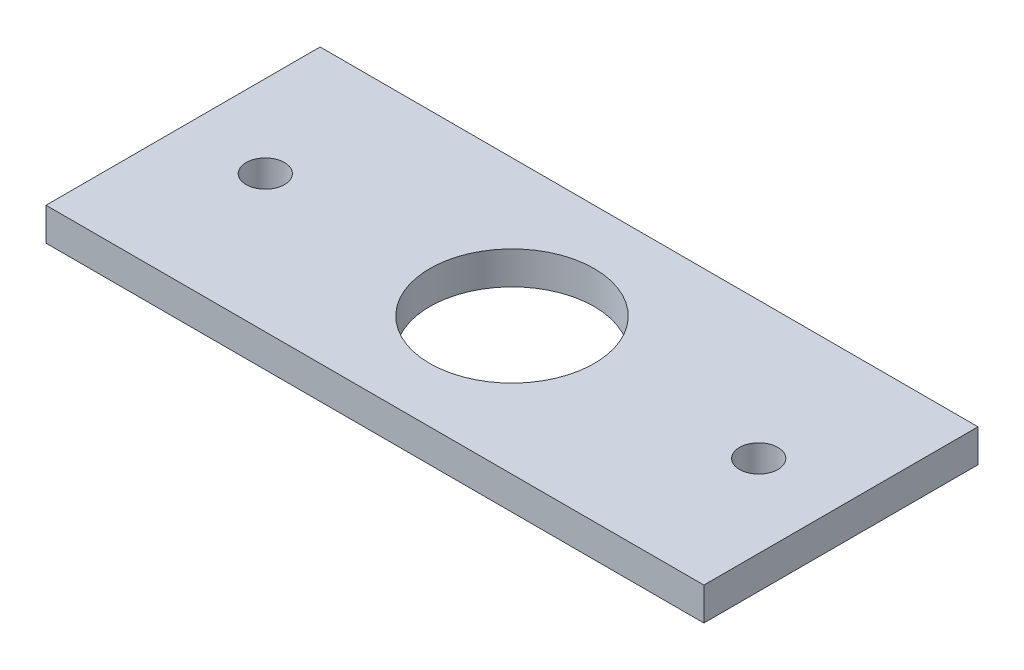
SolidWorks part; units mm, degrees
ref_plane "Front Plane" through (0, 0, 0) normal (0, 0, 1) x (1, 0, 0)
ref_plane "Top Plane" through (0, 0, 0) normal (0, 1, 0) x (1, 0, 0)
ref_plane "Right Plane" through (0, 0, 0) normal (1, 0, 0) x (0, 0, -1)
sketch "Sketch1" plane through (0, 0, 0) normal (0, 1, 0) x (1, 0, 0)
  line L0 (0, -55) -> (0, 55) construction
  line L1 (30, -12.5) -> (-30, -12.5)
  line L2 (30, -12.5) -> (30, 12.5)
  line L3 (30, 12.5) -> (-30, 12.5)
  line L4 (-30, -12.5) -> (-30, 12.5)
  line L5 (30, -12.5) -> (-30, 12.5) construction
  line L6 (30, 12.5) -> (-30, -12.5) construction
  line L7 (-22.5, 0) -> (0, 0) construction
  circle A0 centre (0, 0) radius 7.5
  circle A1 centre (-22.5, 0) radius 1.75
  circle A2 centre (22.5, 0) radius 1.75
  dimension "D3" = 15
  dimension "D4" = 3.5
  dimension "D1" = 25
  dimension "D2" = 60
  dimension "D5" = 45
extrude "Boss-Extrude1" add sketch "Sketch1" along normal blind 3
